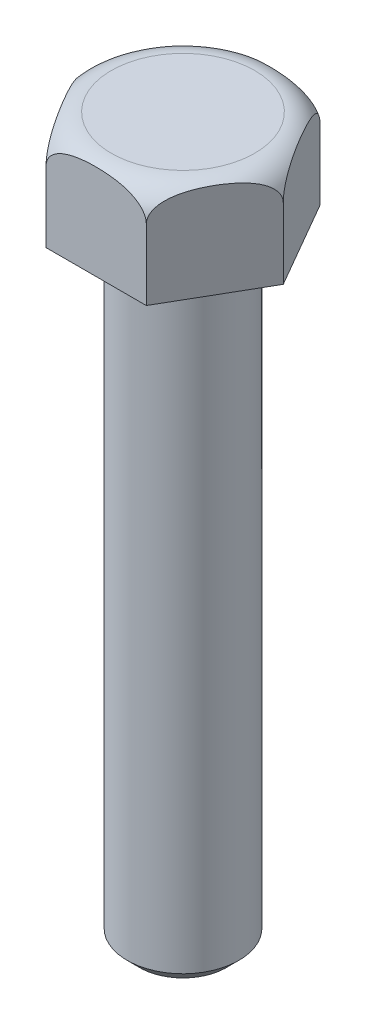
SolidWorks part; units mm, degrees
ref_plane "Front Plane" through (0, 0, 0) normal (0, 0, 1) x (1, 0, 0)
ref_plane "Top Plane" through (0, 0, 0) normal (0, 1, 0) x (1, 0, 0)
ref_plane "Right Plane" through (0, 0, 0) normal (1, 0, 0) x (0, 0, -1)
sketch "Sketch1" plane through (0, 0, 0) normal (0, 1, 0) x (1, 0, 0)
  line L1 (4.0415, 0) -> (2.0207, 3.5)
  line L2 (2.0207, 3.5) -> (-2.0207, 3.5)
  line L3 (-2.0207, 3.5) -> (-4.0415, 0)
  line L4 (-4.0415, 0) -> (-2.0207, -3.5)
  line L5 (-2.0207, -3.5) -> (2.0207, -3.5)
  line L6 (2.0207, -3.5) -> (4.0415, 0)
  circle A0 centre (0, 0) radius 3.5 construction
  dimension "D1" = 7
extrude "Boss-Extrude1" add sketch "Sketch1" along normal blind 4
sketch "Sketch2" plane through (0, 0, 0) normal (0, -1, 0) x (1, 0, 0)
  circle A0 centre (0, 0) radius 2.25
  dimension "D1" = 4.5
extrude "Boss-Extrude2" add sketch "Sketch2" along normal blind 25
cosmetic thread "Cosmetic Thread1" parameters "D1"=25, "D2"=3.22
chamfer "Chamfer1" distance 0.5 angle 45 1 edges at (0, -25, -2.25)
sketch "Sketch3" plane through (0, 0, 0) normal (0, 0, 1) x (1, 0, 0)
  line L0 (0, 0) -> (0, 6.3886) construction
  line L1 (2.0207, 4) -> (4.0415, 4) construction
  line L2 (4.0415, 4) -> (4.0415, 0) construction
  line L3 (2.8915, 4) -> (4.0415, 4)
  line L4 (4.0415, 4) -> (4.0415, 2.85)
  arc A1 (2.8915, 4) -> (4.0415, 2.85) centre (2.8915, 2.85) cw
  dimension "D1" = 1.15
revolve "Cut-Revolve1" cut sketch "Sketch3" angle 360 about L0
